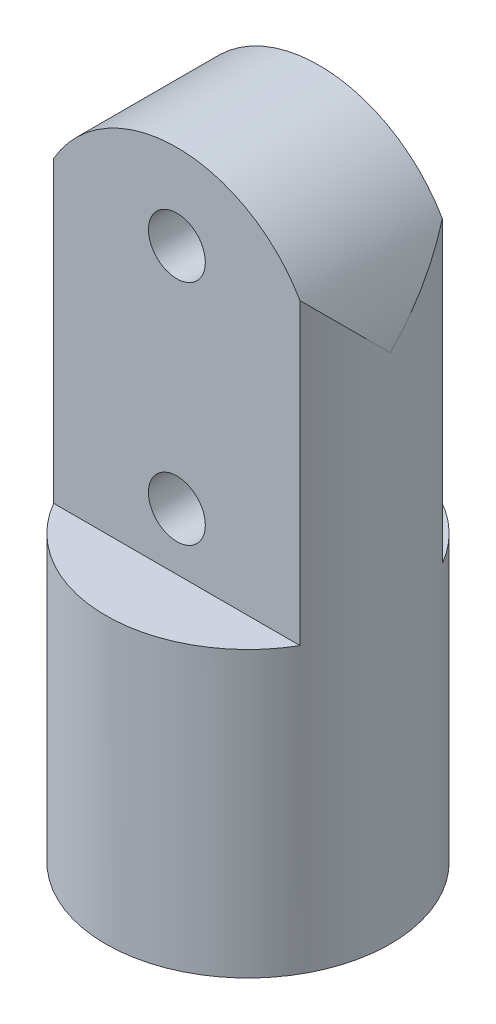
SolidWorks part; units mm, degrees
ref_plane "前视基准面" through (0, 0, 0) normal (0, 0, 1) x (1, 0, 0)
ref_plane "上视基准面" through (0, 0, 0) normal (0, 1, 0) x (1, 0, 0)
ref_plane "右视基准面" through (0, 0, 0) normal (1, 0, 0) x (0, 0, -1)
other "Configuration Table"
sketch "草图1" plane through (0, 0, 0) normal (0, 1, 0) x (1, 0, 0)
  circle A0 centre (0, 0) radius 25
  circle A1 centre (0, 0) radius 10
  dimension "D1" = 20
  dimension "D2" = 50
extrude "凸台-拉伸1" add sketch "草图1" along normal blind 50
sketch "草图2" plane through (0, 0, 0) normal (0, 0, 1) x (1, 0, 0)
  line L0 (-25, 50) -> (25, 50)
  line L1 (25, 50) -> (25, 90)
  line L2 (-25, 50) -> (-25, 90)
  arc A0 (-25, 90) -> (25, 90) centre (0, 90) cw
  dimension "D1" = 40
extrude "凸台-拉伸2" add sketch "草图2" along normal mid plane 25
sketch "草图4" plane through (0, 50, 0) normal (0, -1, 0) x (1, 0, 0)
  line L0 (25, -12.5) -> (25, 0) construction
  line L1 (21.6506, -12.5) -> (25, -12.5) construction
  line L2 (-25, -12.5) -> (-21.6506, -12.5) construction
  line L3 (-25, 0) -> (-25, -12.5) construction
  line L4 (-25, 12.5) -> (-25, 0) construction
  line L5 (-21.6506, 12.5) -> (-25, 12.5) construction
  line L6 (25, 12.5) -> (21.6506, 12.5) construction
  line L7 (25, 0) -> (25, 12.5) construction
  line L8 (25, -12.5) -> (25, 0)
  line L9 (21.6506, -12.5) -> (25, -12.5)
  line L10 (-25, -12.5) -> (-21.6506, -12.5)
  line L11 (-25, 0) -> (-25, -12.5)
  line L12 (-25, 12.5) -> (-25, 0)
  line L13 (-21.6506, 12.5) -> (-25, 12.5)
  line L14 (25, 12.5) -> (21.6506, 12.5)
  line L15 (25, 0) -> (25, 12.5)
  arc A0 (21.6506, -12.5) -> (25, 0) centre (0, 0) ccw construction
  arc A1 (-25, 0) -> (-21.6506, -12.5) centre (0, 0) ccw construction
  arc A2 (-21.6506, 12.5) -> (-25, 0) centre (0, 0) ccw construction
  arc A3 (25, 0) -> (21.6506, 12.5) centre (0, 0) ccw construction
  arc A4 (21.6506, -12.5) -> (25, 0) centre (0, 0) ccw
  arc A5 (-25, 0) -> (-21.6506, -12.5) centre (0, 0) ccw
  arc A6 (-21.6506, 12.5) -> (-25, 0) centre (0, 0) ccw
  arc A7 (25, 0) -> (21.6506, 12.5) centre (0, 0) ccw
extrude "切除-拉伸1" cut sketch "草图4" against normal through all contours A4 L9 L8 | A6 L13 L12 | A5 L11 L10
sketch "草图5" plane through (0, 0, 12.5) normal (0, 0, 1) x (1, 0, 0)
  line L0 (21.6506, 50) -> (-21.6506, 50) construction
  circle A2 centre (0, 100) radius 5
  circle A3 centre (0, 60) radius 5
  point P5 (0, 0)
  point P9 (0, 0)
  dimension "D1" = 10
  dimension "D2" = 10
  dimension "D3" = 10
  dimension "D4" = 40
extrude "切除-拉伸2" cut sketch "草图5" against normal through all
